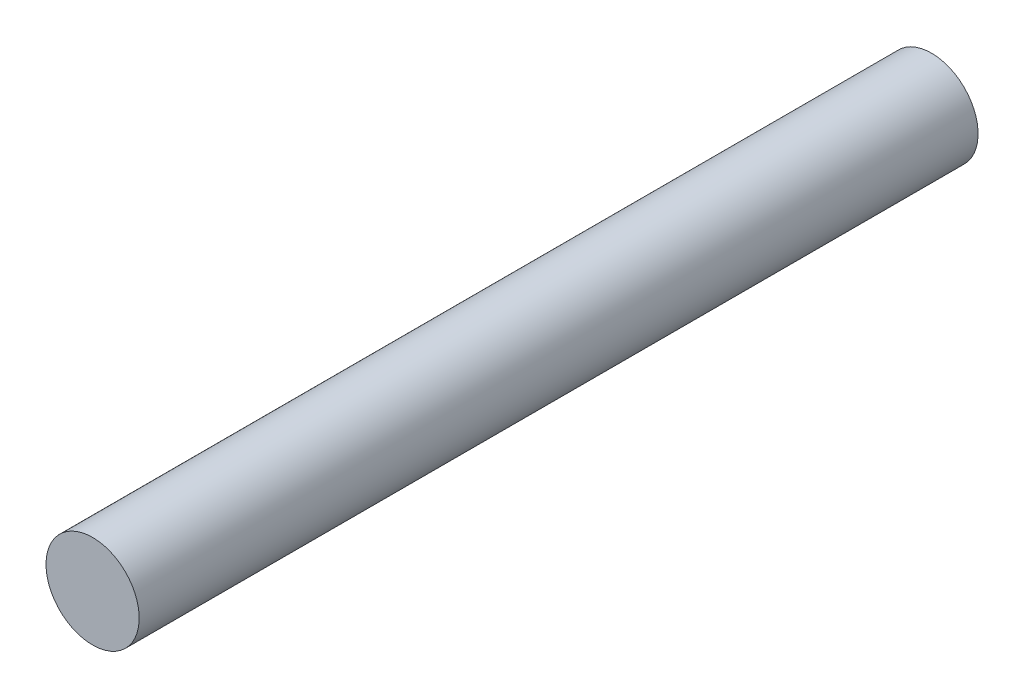
SolidWorks part; units mm, degrees
material "AISI 304"
ref_plane "Front" through (0, 0, 0) normal (0, 0, 1) x (1, 0, 0)
ref_plane "Top" through (0, 0, 0) normal (0, 1, 0) x (1, 0, 0)
ref_plane "Right" through (0, 0, 0) normal (1, 0, 0) x (0, 0, -1)
sketch "Sketch1" plane through (0, 0, 0) normal (0, 0, 1) x (1, 0, 0)
  circle A0 centre (0, 0) radius 2.5
  dimension "D1" = 5
extrude "Boss-Extrude1" add sketch "Sketch1" along normal blind 45
